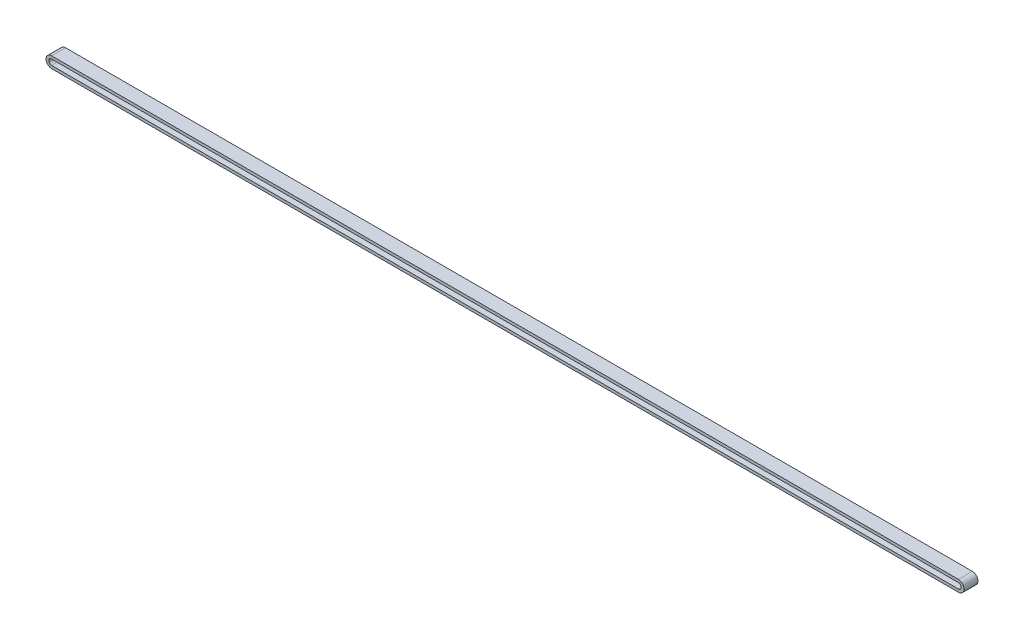
SolidWorks part; units mm, degrees
ref_plane "前视基准面" through (0, 0, 0) normal (0, 0, 1) x (1, 0, 0)
ref_plane "上视基准面" through (0, 0, 0) normal (0, 1, 0) x (1, 0, 0)
ref_plane "右视基准面" through (0, 0, 0) normal (1, 0, 0) x (0, 0, -1)
sketch "草图1" plane through (0, 0, 0) normal (0, 0, 1) x (1, 0, 0)
  line L0 (0, 1) -> (325.0023, 1)
  line L1 (0, -1) -> (325.0023, -1)
  line L2 (0, 2) -> (325.0023, 2)
  line L3 (0, -2) -> (325.0023, -2)
  line L4 (325.0023, 2) -> (325.0023, -2)
  circle A0 centre (0, 0) radius 1
  circle A1 centre (0, 0) radius 2
  circle A2 centre (325.0023, 0) radius 1
  circle A3 centre (325.0023, 0) radius 2
extrude "凸台-拉伸1" add sketch "草图1" along normal blind 5 contours L4 A3 A2 | A3 L2 A1 L0 | L4 A3 L0 | L1 A3 L4 | A3 L1 A1 L3 | L0 A1 L1 A0
